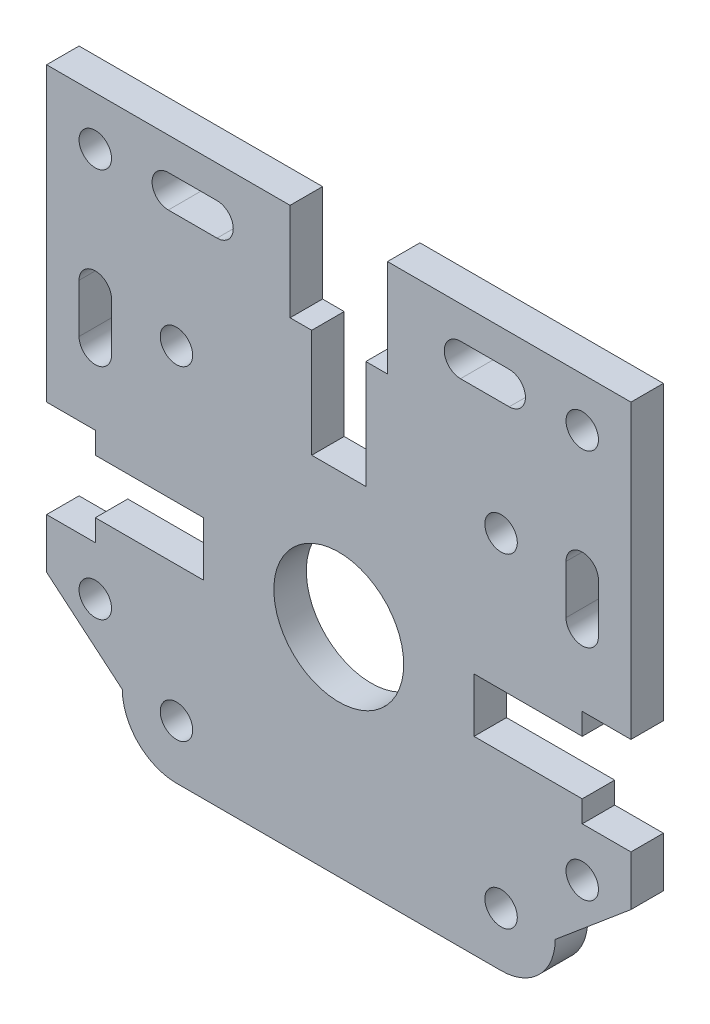
SolidWorks part; units mm, degrees
ref_plane "Alzado" through (0, 0, 0) normal (0, 0, 1) x (1, 0, 0)
ref_plane "Planta" through (0, 0, 0) normal (0, 1, 0) x (1, 0, 0)
ref_plane "Vista lateral" through (0, 0, 0) normal (1, 0, 0) x (0, 0, -1)
sketch "Model" plane through (0, 0, 0) normal (0, 0, 1) x (1, 0, 0)
  line L0 (187.9529, 215.6113) -> (189.9529, 215.6113)
  line L1 (189.9529, 215.6113) -> (189.9529, 224.6113)
  line L2 (189.9529, 224.6113) -> (212.4529, 224.6113)
  line L3 (212.4529, 224.6113) -> (212.4529, 197.6113)
  line L4 (212.4529, 197.6113) -> (207.9529, 197.6113)
  line L5 (207.9529, 197.6113) -> (207.9529, 195.6113)
  line L6 (207.9529, 195.6113) -> (197.9529, 195.6113)
  line L7 (197.9529, 195.6113) -> (197.9529, 190.6113)
  line L8 (197.9529, 190.6113) -> (207.9529, 190.6113)
  line L9 (207.9529, 190.6113) -> (207.9529, 188.6113)
  line L10 (207.9529, 188.6113) -> (212.4529, 188.6113)
  line L11 (212.4529, 188.6113) -> (212.4529, 183.9956)
  line L12 (212.4529, 183.9956) -> (205.4529, 178.1113)
  line L13 (200.4529, 173.1113) -> (170.4529, 173.1113)
  line L14 (165.4529, 178.1113) -> (158.4529, 183.9956)
  line L15 (158.4529, 183.9956) -> (158.4529, 188.6113)
  line L16 (158.4529, 188.6113) -> (162.9529, 188.6113)
  line L17 (162.9529, 188.6113) -> (162.9529, 190.6113)
  line L18 (162.9529, 190.6113) -> (172.9529, 190.6113)
  line L19 (172.9529, 190.6113) -> (172.9529, 195.6113)
  line L20 (172.9529, 195.6113) -> (162.9529, 195.6113)
  line L21 (162.9529, 195.6113) -> (162.9529, 197.6113)
  line L22 (162.9529, 197.6113) -> (158.4529, 197.6113)
  line L23 (158.4529, 197.6113) -> (158.4529, 224.6113)
  line L24 (158.4529, 224.6113) -> (180.9529, 224.6113)
  line L25 (180.9529, 224.6113) -> (180.9529, 215.6113)
  line L26 (180.9529, 215.6113) -> (182.9529, 215.6113)
  line L27 (182.9529, 215.6113) -> (182.9529, 205.6113)
  line L28 (182.9529, 205.6113) -> (187.9529, 205.6113)
  line L29 (187.9529, 205.6113) -> (187.9529, 215.6113)
  line L30 (169.7029, 221.6113) -> (174.2029, 221.6113)
  line L31 (169.7029, 218.6113) -> (174.2029, 218.6113)
  line L32 (164.4529, 208.8613) -> (164.4529, 204.3613)
  line L33 (161.4529, 204.3613) -> (161.4529, 208.8613)
  line L34 (196.7029, 218.6113) -> (201.2029, 218.6113)
  line L35 (196.7029, 221.6113) -> (201.2029, 221.6113)
  line L36 (206.4529, 208.8613) -> (206.4529, 204.3613)
  line L37 (209.4529, 204.3613) -> (209.4529, 208.8613)
  circle A0 centre (207.9529, 220.1113) radius 1.5
  circle A1 centre (200.4529, 208.1113) radius 1.5
  circle A2 centre (207.9529, 184.1113) radius 1.5
  circle A3 centre (185.4529, 193.1113) radius 6
  circle A4 centre (200.4529, 178.1113) radius 1.5
  circle A5 centre (162.9529, 220.1113) radius 1.5
  circle A6 centre (170.4529, 208.1113) radius 1.5
  circle A7 centre (162.9529, 184.1113) radius 1.5
  circle A8 centre (170.4529, 178.1113) radius 1.5
  arc A9 (200.4529, 173.1113) -> (205.4529, 178.1113) centre (200.4529, 178.1113) ccw
  arc A10 (165.4529, 178.1113) -> (170.4529, 173.1113) centre (170.4529, 178.1113) ccw
  arc A11 (174.2029, 218.6113) -> (174.2029, 221.6113) centre (174.2029, 220.1113) ccw
  arc A12 (169.7029, 221.6113) -> (169.7029, 218.6113) centre (169.7029, 220.1113) ccw
  arc A13 (196.7029, 221.6113) -> (196.7029, 218.6113) centre (196.7029, 220.1113) ccw
  arc A14 (201.2029, 218.6113) -> (201.2029, 221.6113) centre (201.2029, 220.1113) ccw
  arc A15 (206.4529, 204.3613) -> (209.4529, 204.3613) centre (207.9529, 204.3613) ccw
  arc A16 (209.4529, 208.8613) -> (206.4529, 208.8613) centre (207.9529, 208.8613) ccw
  arc A17 (161.4529, 204.3613) -> (164.4529, 204.3613) centre (162.9529, 204.3613) ccw
  arc A18 (164.4529, 208.8613) -> (161.4529, 208.8613) centre (162.9529, 208.8613) ccw
extrude "Saliente-Extruir1" add sketch "Model" along normal blind 3
